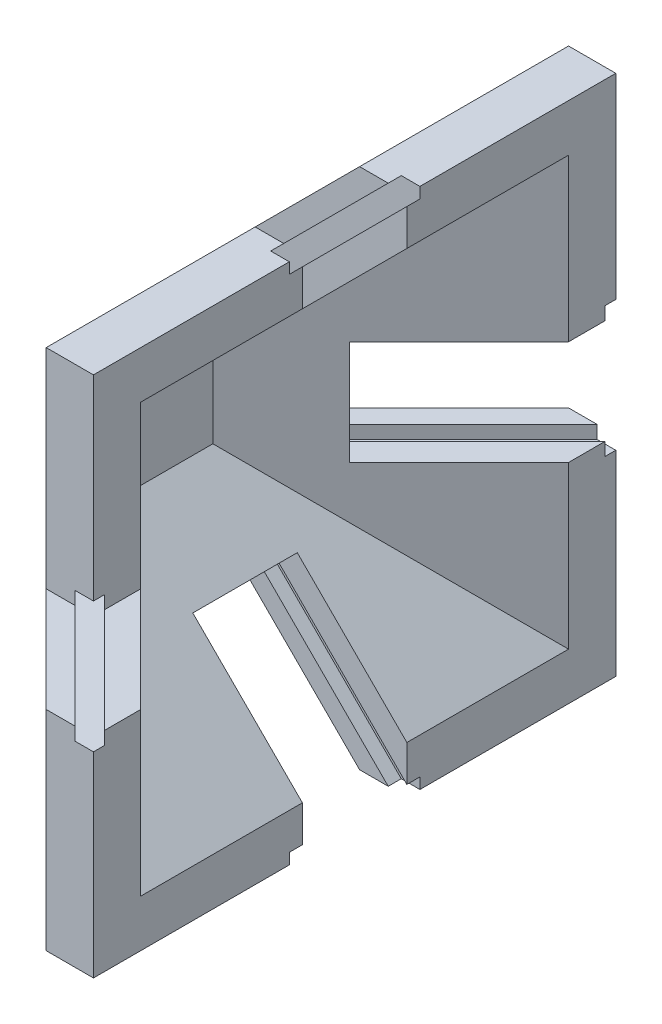
SolidWorks part; units mm, degrees
ref_plane "Front Plane" through (0, 0, 0) normal (0, 0, 1) x (1, 0, 0)
ref_plane "Top Plane" through (0, 0, 0) normal (0, 1, 0) x (1, 0, 0)
ref_plane "Right Plane" through (0, 0, 0) normal (1, 0, 0) x (0, 0, -1)
sketch "Sketch1" plane through (0, 0, 0) normal (0, 0, 1) x (1, 0, 0)
  line L0 (14.7414, -14.7414) -> (16.1783, -13.3046)
  line L1 (16.1783, -13.3046) -> (15.0822, -12.2086)
  line L2 (15.0822, -12.2086) -> (16.4293, -10.8615)
  line L3 (16.4293, -10.8615) -> (17.5253, -11.9575)
  line L4 (17.5253, -11.9575) -> (18.6029, -10.8799)
  line L5 (18.6029, -10.8799) -> (17.5069, -9.7839)
  line L6 (17.5069, -9.7839) -> (17.8661, -9.4247)
  line L7 (17.8661, -9.4247) -> (18.9621, -10.5207)
  line L8 (18.9621, -10.5207) -> (19.3376, -10.1452)
  line L9 (21.1796, -21.1796) -> (25.7758, -16.5834) construction
  line L10 (14.7414, -14.7414) -> (27.6178, -27.6178)
  line L11 (19.3376, -10.1452) -> (32.214, -23.0216)
  line L12 (31.8386, -23.3971) -> (32.214, -23.0216)
  line L13 (33.2528, -24.8113) -> (31.8386, -23.3971)
  line L14 (32.8936, -25.1705) -> (33.2528, -24.8113)
  line L15 (31.4793, -23.7563) -> (32.8936, -25.1705)
  line L16 (30.4017, -24.834) -> (31.4793, -23.7563)
  line L17 (31.8159, -26.2482) -> (30.4017, -24.834)
  line L18 (30.4689, -27.5952) -> (31.8159, -26.2482)
  line L19 (29.0547, -26.181) -> (30.4689, -27.5952)
  line L20 (27.6178, -27.6178) -> (29.0547, -26.181)
  line L21 (79.6776, 0) -> (-77.6267, 0) construction
  line L22 (21.1796, 21.1796) -> (25.7758, 16.5834) construction
  line L23 (27.6178, 27.6178) -> (29.0547, 26.181)
  line L24 (29.0547, 26.181) -> (30.4689, 27.5952)
  line L25 (30.4689, 27.5952) -> (31.8159, 26.2482)
  line L26 (31.8159, 26.2482) -> (30.4017, 24.834)
  line L27 (30.4017, 24.834) -> (31.4793, 23.7563)
  line L28 (31.4793, 23.7563) -> (32.8936, 25.1705)
  line L29 (32.8936, 25.1705) -> (33.2528, 24.8113)
  line L30 (33.2528, 24.8113) -> (31.8386, 23.3971)
  line L31 (31.8386, 23.3971) -> (32.214, 23.0216)
  line L32 (19.3376, 10.1452) -> (32.214, 23.0216)
  line L33 (14.7414, 14.7414) -> (27.6178, 27.6178)
  line L34 (18.9621, 10.5207) -> (19.3376, 10.1452)
  line L35 (17.8661, 9.4247) -> (18.9621, 10.5207)
  line L36 (17.5069, 9.7839) -> (17.8661, 9.4247)
  line L37 (18.6029, 10.8799) -> (17.5069, 9.7839)
  line L38 (17.5253, 11.9575) -> (18.6029, 10.8799)
  line L39 (16.4293, 10.8615) -> (17.5253, 11.9575)
  line L40 (15.0822, 12.2086) -> (16.4293, 10.8615)
  line L41 (16.1783, 13.3046) -> (15.0822, 12.2086)
  line L42 (14.7414, 14.7414) -> (16.1783, 13.3046)
  line L43 (19.9648, 12.7) -> (19.9648, -12.7) construction
  line L44 (19.9648, -12.7) -> (42.2648, -35) construction
  line L45 (42.2648, -35) -> (79.6776, -35) construction
  line L46 (79.6776, -35) -> (79.6776, -3.3) construction
  line L47 (79.6776, -3.3) -> (79.6776, 3.3) construction
  line L48 (79.6776, 35) -> (79.6776, 3.3) construction
  line L49 (42.2648, 35) -> (79.6776, 35) construction
  line L50 (19.9648, 12.7) -> (42.2648, 35) construction
  line L51 (19.9648, -12.7) -> (169.5862, 27.3909) construction
  line L52 (19.9648, 12.7) -> (169.5862, -27.3909) construction
  line L53 (14.7414, 14.7414) -> (0, 0) construction
  line L54 (0, 0) -> (14.7414, -14.7414) construction
  line L55 (19.3376, 10.1452) -> (9.1924, 0) construction
  line L56 (9.1924, 0) -> (19.3376, -10.1452) construction
  line L58 (32.214, 23.0216) -> (44.1924, 35) construction
  line L59 (32.214, -23.0216) -> (44.1924, -35) construction
  line L60 (15.7558, 11.535) -> (31.1424, 26.9217) construction
  line L61 (15.7558, -11.535) -> (31.1424, -26.9217) construction
  point P46 (19.9648, -12.7)
  point P47 (19.9648, 12.7)
  dimension "D1" = 1.524
  dimension "D2" = 1.905
  dimension "D3" = 1.55
  dimension "D4" = 2
  dimension "D5" = 21.76
  dimension "D6" = 3.8
  dimension "D7" = 1.2
  dimension "D8" = 6.5
  dimension "D9" = 2.032
  dimension "D10" = 0.508
  dimension "D11" = 30
  dimension "D12" = 70
  dimension "D13" = 6.6
  dimension "D14" = 25.4
sketch "Sketch2" plane through (0, 0, 0) normal (0, 1, 0) x (1, 0, 0)
  line L0 (14.7414, -14.7414) -> (16.1783, -13.3046)
  line L1 (16.1783, -13.3046) -> (15.0822, -12.2086)
  line L2 (15.0822, -12.2086) -> (16.4293, -10.8615)
  line L3 (16.4293, -10.8615) -> (17.5253, -11.9575)
  line L4 (17.5253, -11.9575) -> (18.6029, -10.8799)
  line L5 (18.6029, -10.8799) -> (17.5069, -9.7839)
  line L6 (17.5069, -9.7839) -> (17.8661, -9.4247)
  line L7 (17.8661, -9.4247) -> (18.9621, -10.5207)
  line L8 (18.9621, -10.5207) -> (19.3376, -10.1452)
  line L9 (21.1796, -21.1796) -> (25.7758, -16.5834) construction
  line L10 (14.7414, -14.7414) -> (27.6178, -27.6178)
  line L11 (19.3376, -10.1452) -> (32.214, -23.0216)
  line L12 (31.8386, -23.3971) -> (32.214, -23.0216)
  line L13 (33.2528, -24.8113) -> (31.8386, -23.3971)
  line L14 (32.8936, -25.1705) -> (33.2528, -24.8113)
  line L15 (31.4793, -23.7563) -> (32.8936, -25.1705)
  line L16 (30.4017, -24.834) -> (31.4793, -23.7563)
  line L17 (31.8159, -26.2482) -> (30.4017, -24.834)
  line L18 (30.4689, -27.5952) -> (31.8159, -26.2482)
  line L19 (29.0547, -26.181) -> (30.4689, -27.5952)
  line L20 (27.6178, -27.6178) -> (29.0547, -26.181)
  line L21 (79.6776, 0) -> (-77.6267, 0) construction
  line L22 (21.1796, 21.1796) -> (25.7758, 16.5834) construction
  line L23 (27.6178, 27.6178) -> (29.0547, 26.181)
  line L24 (29.0547, 26.181) -> (30.4689, 27.5952)
  line L25 (30.4689, 27.5952) -> (31.8159, 26.2482)
  line L26 (31.8159, 26.2482) -> (30.4017, 24.834)
  line L27 (30.4017, 24.834) -> (31.4793, 23.7563)
  line L28 (31.4793, 23.7563) -> (32.8936, 25.1705)
  line L29 (32.8936, 25.1705) -> (33.2528, 24.8113)
  line L30 (33.2528, 24.8113) -> (31.8386, 23.3971)
  line L31 (31.8386, 23.3971) -> (32.214, 23.0216)
  line L32 (19.3376, 10.1452) -> (32.214, 23.0216)
  line L33 (14.7414, 14.7414) -> (27.6178, 27.6178)
  line L34 (18.9621, 10.5207) -> (19.3376, 10.1452)
  line L35 (17.8661, 9.4247) -> (18.9621, 10.5207)
  line L36 (17.5069, 9.7839) -> (17.8661, 9.4247)
  line L37 (18.6029, 10.8799) -> (17.5069, 9.7839)
  line L38 (17.5253, 11.9575) -> (18.6029, 10.8799)
  line L39 (16.4293, 10.8615) -> (17.5253, 11.9575)
  line L40 (15.0822, 12.2086) -> (16.4293, 10.8615)
  line L41 (16.1783, 13.3046) -> (15.0822, 12.2086)
  line L42 (14.7414, 14.7414) -> (16.1783, 13.3046)
  line L43 (19.9648, 12.7) -> (19.9648, -12.7) construction
  line L44 (19.9648, -12.7) -> (42.2648, -35) construction
  line L45 (42.2648, -35) -> (79.6776, -35) construction
  line L46 (79.6776, -35) -> (79.6776, -3.3) construction
  line L47 (79.6776, -3.3) -> (79.6776, 3.3) construction
  line L48 (79.6776, 35) -> (79.6776, 3.3) construction
  line L49 (42.2648, 35) -> (79.6776, 35) construction
  line L50 (19.9648, 12.7) -> (42.2648, 35) construction
  line L51 (19.9648, -12.7) -> (169.5862, 27.3909) construction
  line L52 (19.9648, 12.7) -> (169.5862, -27.3909) construction
  line L53 (14.7414, 14.7414) -> (0, 0) construction
  line L54 (0, 0) -> (14.7414, -14.7414) construction
  line L55 (19.3376, 10.1452) -> (9.1924, 0) construction
  line L56 (9.1924, 0) -> (19.3376, -10.1452) construction
  line L57 (27.6178, 27.6178) -> (42.279, 42.279) construction
  line L59 (32.214, -23.0216) -> (44.1924, -35) construction
  line L60 (15.7558, 11.535) -> (31.1424, 26.9217) construction
  line L61 (15.7558, -11.535) -> (31.1424, -26.9217) construction
  line L62 (29.9962, 25.4) -> (25.4, 25.4) construction
  line L63 (29.9962, 25.4) -> (29.9962, 20.8038) construction
  line L64 (9.1924, 0) -> (47.358, 38.1656) construction
  point P46 (19.9648, -12.7)
  point P47 (19.9648, 12.7)
  point P63 (29.9962, 25.4)
  dimension "D1" = 1.524
  dimension "D2" = 1.905
  dimension "D3" = 1.55
  dimension "D4" = 2
  dimension "D5" = 21.76
  dimension "D6" = 3.8
  dimension "D7" = 1.2
  dimension "D8" = 6.5
  dimension "D9" = 2.032
  dimension "D10" = 0.508
  dimension "D11" = 30
  dimension "D12" = 70
  dimension "D13" = 6.6
  dimension "D14" = 25.4
  dimension "D15" = 25.4
sketch "Sketch3" plane through (0, 0, 0) normal (1, 0, 0) x (0, 0, -1)
  line L1 (-25.4, 25.4) -> (25.4, 25.4)
  line L2 (-25.4, 25.4) -> (-25.4, -25.4)
  line L3 (-25.4, -25.4) -> (25.4, -25.4)
  line L4 (25.4, 25.4) -> (25.4, -25.4)
  line L5 (-25.4, 25.4) -> (25.4, -25.4) construction
  line L6 (-25.4, -25.4) -> (25.4, 25.4) construction
  point P0 (0, 0)
extrude "Boss-Extrude1" add sketch "Sketch3" along normal up to vertex (29.9962 mm away) up to point (29.9962, 0, -25.4)
ref_plane "Plane1" through (12.7, 0, 0) normal (1, 0, 0) x (0, 0, -1)
sketch "Sketch4" plane through (12.7, 0, 0) normal (1, 0, 0) x (0, 0, -1)
  line L1 (-3.5076, 3.5076) -> (3.5076, 3.5076)
  line L2 (-3.5076, 3.5076) -> (-3.5076, -3.5076)
  line L3 (-3.5076, -3.5076) -> (3.5076, -3.5076)
  line L4 (3.5076, 3.5076) -> (3.5076, -3.5076)
  line L5 (-3.5076, 3.5076) -> (3.5076, -3.5076) construction
  line L6 (-3.5076, -3.5076) -> (3.5076, 3.5076) construction
  point P0 (0, 0)
  point P8 (3.5076, 0)
ref_plane "Plane2" through (29.9962, 0, 0) normal (1, 0, 0) x (0, 0, -1)
sketch "Sketch5" plane through (29.9962, 0, 0) normal (1, 0, 0) x (0, 0, -1)
  line L1 (-20.8038, 20.8038) -> (20.8038, 20.8038)
  line L2 (-20.8038, 20.8038) -> (-20.8038, -20.8038)
  line L3 (-20.8038, -20.8038) -> (20.8038, -20.8038)
  line L4 (20.8038, 20.8038) -> (20.8038, -20.8038)
  line L5 (-20.8038, 20.8038) -> (20.8038, -20.8038) construction
  line L6 (-20.8038, -20.8038) -> (20.8038, 20.8038) construction
  point P0 (0, 0)
  point P8 (20.8038, 0)
loft "Cut-Loft1" cut profiles "Sketch4", "Sketch5"
sketch "Sketch6" plane through (0, 25.4, 0) normal (0, 1, 0) x (1, 0, 0)
  line L0 (25.4, -25.4) -> (0, 0)
  line L1 (29.9962, -25.4) -> (0, -25.4) construction
  line L2 (0, 25.4) -> (0, -25.4) construction
  line L3 (14.7414, -14.7414) -> (27.6178, -27.6178) construction
  line L4 (0, 0) -> (0, -25.4)
  line L5 (0, -25.4) -> (25.4, -25.4)
extrude "Cut-Extrude1" cut sketch "Sketch6" against normal through all
sketch "Sketch7" plane through (0, 0, 0) normal (0, 0, 1) x (1, 0, 0)
  line L0 (0, 0) -> (-117.5373, 0) construction
pattern_circular "CirPattern1" count 4 over 360 about axis through (0, 0, 0) along (1, 0, 0) of "Cut-Extrude1"
ref_plane "Plane3" through (6.35, 0, 0) normal (1, 0, 0) x (0, 0, -1)
sketch "Sketch8" plane through (6.35, 0, 0) normal (1, 0, 0) x (0, 0, -1)
  line L1 (6.35, 6.35) -> (-6.35, 6.35)
  line L2 (6.35, 6.35) -> (6.35, -6.35)
  line L3 (6.35, -6.35) -> (-6.35, -6.35)
  line L4 (-6.35, 6.35) -> (-6.35, -6.35)
  line L5 (6.35, 6.35) -> (-6.35, -6.35) construction
  line L6 (6.35, -6.35) -> (-6.35, 6.35) construction
  line L7 (3.5076, -3.5076) -> (20.8038, -20.8038) construction
  point P0 (0, 0)
extrude "Cut-Extrude2" cut sketch "Sketch8" against normal through all
ref_plane "Plane4" through (31.1424, 0, 26.9217) normal (0.7071, 0, 0.7071) x (0.7071, 0, -0.7071)
sketch "Sketch9" plane through (31.1424, 0, 26.9217) normal (0.7071, 0, 0.7071) x (0.7071, 0, -0.7071)
  line L0 (-1.016, 5.08) -> (-1.016, 6.35)
  line L1 (-1.016, 6.35) -> (1.016, 6.35)
  line L2 (1.016, 6.35) -> (1.016, 5.08)
  line L3 (1.016, 5.08) -> (3.5155, 5.08)
  line L4 (3.5155, 5.08) -> (3.5155, -5.08)
  line L5 (3.5155, -5.08) -> (1.016, -5.08)
  line L6 (1.016, -5.08) -> (1.016, -6.35)
  line L7 (1.016, -6.35) -> (-1.016, -6.35)
  line L8 (-1.016, -6.35) -> (-1.016, -5.08)
  line L9 (-1.016, -5.08) -> (-3.5155, -5.08)
  line L10 (-3.5155, -5.08) -> (-3.5155, 5.08)
  line L11 (-3.5155, 5.08) -> (-1.016, 5.08)
  line L12 (0, 0) -> (0, -23.1099) construction
  line L13 (0, 0) -> (17.1064, 0) construction
  line L15 (3.5155, 20.8038) -> (3.5155, -20.8038) construction
  dimension "D1" = 12.7
  dimension "D2" = 1.27
  dimension "D3" = 2.032
extrude "Cut-Extrude3" cut sketch "Sketch9" against normal up to vertex (20.21 mm away) and the other way through all up to point (16.1783, 0, 13.3046)
sketch "Sketch10" plane through (31.1424, 0, 26.9217) normal (0.7071, 0, 0.7071) x (0.7071, 0, -0.7071)
  line L0 (-1.016, 6.35) -> (1.016, 6.35)
  line L1 (1.016, 6.35) -> (1.016, -6.35)
  line L2 (1.016, -6.35) -> (-1.016, -6.35)
  line L3 (-1.016, -6.35) -> (-1.016, 6.35)
extrude "Cut-Extrude4" cut sketch "Sketch10" against normal up to vertex (21.76 mm away) up to point (15.0822, 0, 12.2086)
pattern_circular "CirPattern2" count 4 over 360 about axis through (0, 0, 0) along (1, 0, 0) of "Cut-Extrude4", "Cut-Extrude3"
ref_plane "Plane5" through (25.4, 0, 0) normal (1, 0, 0) x (0, 0, -1)
sketch "Sketch11" plane through (25.4, 0, 0) normal (1, 0, 0) x (0, 0, -1)
  line L0 (25.4, 25.4) -> (6.35, 6.35) construction
  line L1 (25.4, 25.4) -> (19.05, 25.4)
  line L2 (25.4, 25.4) -> (25.4, 19.05)
  line L3 (25.4, 19.05) -> (19.05, 19.05)
  line L4 (19.05, 25.4) -> (19.05, 19.05)
  line L5 (25.4, -19.05) -> (19.05, -19.05)
  line L6 (19.05, -25.4) -> (19.05, -19.05)
  line L7 (25.4, -25.4) -> (19.05, -25.4)
  line L8 (25.4, -25.4) -> (25.4, -19.05)
  line L9 (-19.05, -25.4) -> (-19.05, -19.05)
  line L10 (-25.4, -19.05) -> (-19.05, -19.05)
  line L11 (-25.4, -25.4) -> (-25.4, -19.05)
  line L12 (-25.4, -25.4) -> (-19.05, -25.4)
  line L13 (-25.4, 19.05) -> (-19.05, 19.05)
  line L14 (-19.05, 25.4) -> (-19.05, 19.05)
  line L15 (-25.4, 25.4) -> (-19.05, 25.4)
  line L16 (-25.4, 25.4) -> (-25.4, 19.05)
  point P22 (0, 0)
  dimension "D1" = 6.35
  dimension "D2" = 4
extrude "Cut-Extrude5" cut sketch "Sketch11" against normal through all
equation "\"HUB_LENGTH\" = 2"
equation "\"D15@Sketch2\"=1/2*\"HUB_LENGTH\""
